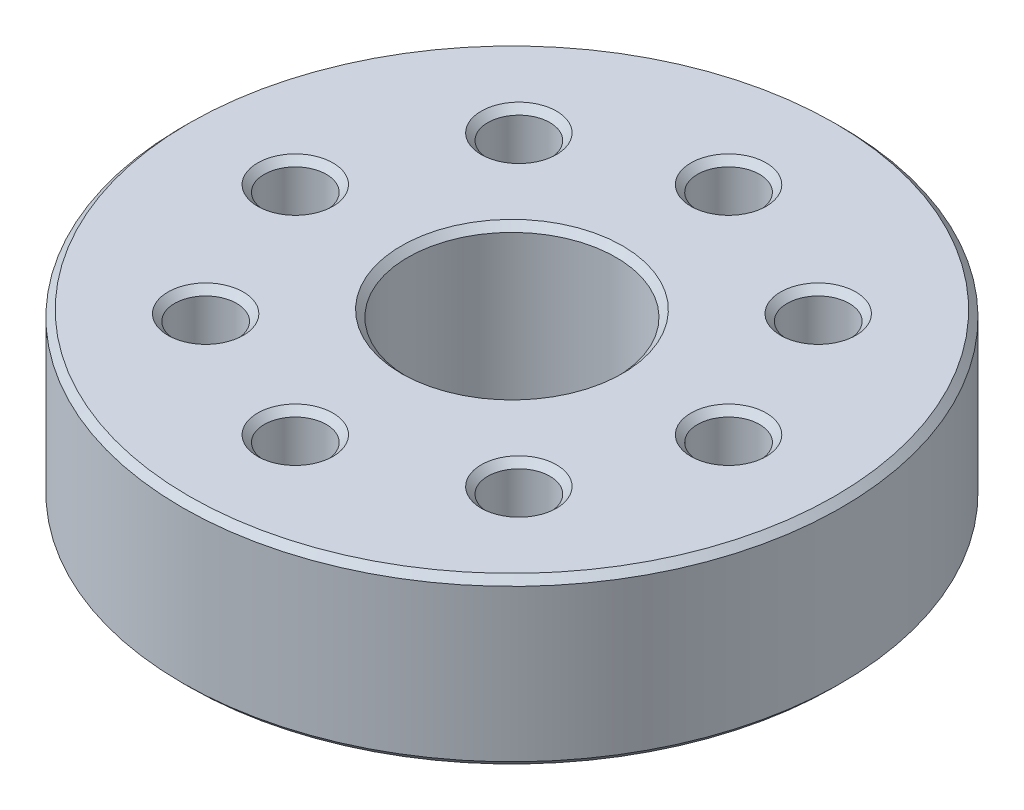
SolidWorks part; units mm, degrees
material "6061 Alloy"
ref_plane "Front Plane" through (0, 0, 0) normal (0, 0, 1) x (1, 0, 0)
ref_plane "Top Plane" through (0, 0, 0) normal (0, 1, 0) x (1, 0, 0)
ref_plane "Right Plane" through (0, 0, 0) normal (1, 0, 0) x (0, 0, -1)
sketch "Sketch1" plane through (0, 0, 0) normal (0, 1, 0) x (1, 0, 0)
  line L0 (6.0228, 5.7563) -> (-5.7563, -6.0228) construction
  line L1 (-5.7563, 6.0228) -> (6.0228, -5.7563) construction
  line L2 (0, 8.3312) -> (0, -8.3312) construction
  line L3 (-8.3312, 0) -> (8.3312, 0) construction
  circle A0 centre (0, 0) radius 12.6746
  circle A1 centre (0, 0) radius 4.0005
  circle A2 centre (0, 8.3312) radius 1.1938
  circle A3 centre (8.3312, 0) radius 1.1938
  circle A4 centre (0, -8.3312) radius 1.1938
  circle A5 centre (-8.3312, 0) radius 1.1938
  circle A7 centre (-5.7563, 6.0228) radius 1.1938
  circle A8 centre (6.0228, 5.7563) radius 1.1938
  circle A9 centre (6.0228, -5.7563) radius 1.1938
  circle A10 centre (-5.7563, -6.0228) radius 1.1938
  dimension "D1" = 8.001
  dimension "D3" = 2.3876
  dimension "D4" = 45
  dimension "D5" = 45
extrude "Boss-Extrude1" add sketch "Sketch1" along normal blind 6.35
chamfer "Chamfer1" distance 0.254 angle 45 20 edges at (-8.3312, 0, 1.1938) (-5.7563, 0, -4.829) (0, 0, -7.1374) (6.0228, 0, -4.5625) (8.3312, 0, 1.1938) (6.0228, 0, 6.9501) (0, 0, 9.525) (-5.7563, 0, 7.2166) (0, 0, 12.6746) (0, 0, 4.0005) (0, 6.35, 4.0005) (6.0228, 6.35, -4.5625) (8.3312, 6.35, 1.1938) (6.0228, 6.35, 6.9501) (0, 6.35, 9.525) (-5.7563, 6.35, 7.2166) (-8.3312, 6.35, 1.1938) (-5.7563, 6.35, -4.829) (0, 6.35, -7.1374) (0, 6.35, 12.6746)
